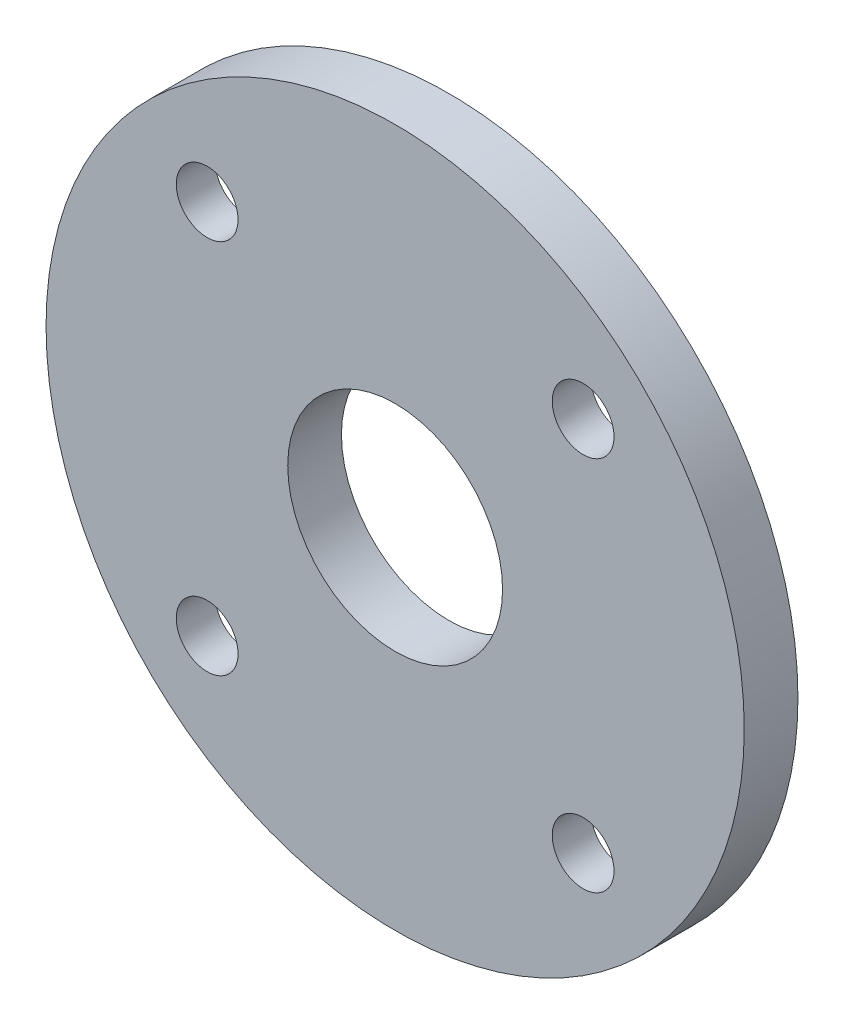
SolidWorks part; units mm, degrees
ref_plane "Front Plane" through (0, 0, 0) normal (0, 0, 1) x (1, 0, 0)
ref_plane "Top Plane" through (0, 0, 0) normal (0, 1, 0) x (1, 0, 0)
ref_plane "Right Plane" through (0, 0, 0) normal (1, 0, 0) x (0, 0, -1)
sketch "Cap_OD26_ID8_thickness2_profile" plane through (0, 0, 0) normal (0, 0, 1) x (1, 0, 0)
  circle A0 centre (0, 0) radius 13
  circle A1 centre (0, 0) radius 4
  dimension "D1" = 26
  dimension "D2" = 8
extrude "Cap_OD26_ID8_thickness2" add sketch "Cap_OD26_ID8_thickness2_profile" along normal blind 2
sketch "Four_M2_capture_holes_profile" plane through (0, 0, 0) normal (0, 0, 1) x (1, 0, 0)
  circle A0 centre (7, 7) radius 1.15
  circle A1 centre (-7, 7) radius 1.15
  circle A2 centre (-7, -7) radius 1.15
  circle A3 centre (7, -7) radius 1.15
  dimension "D1" = 2.3
  dimension "D2" = 2.3
  dimension "D3" = 2.3
  dimension "D4" = 2.3
extrude "Four_M2_capture_holes" cut sketch "Four_M2_capture_holes_profile" along normal through all from offset 50
sketch "Low_profile_head_seats" plane through (0, 0, 0) normal (0, 0, 1) x (1, 0, 0)
  circle A0 centre (7, 7) radius 2.1
  circle A1 centre (-7, 7) radius 2.1
  circle A2 centre (-7, -7) radius 2.1
  circle A3 centre (7, -7) radius 2.1
  dimension "D1" = 4.2
  dimension "D2" = 4.2
  dimension "D3" = 4.2
  dimension "D4" = 4.2
extrude "Head_recess_depth0p55" cut sketch "Low_profile_head_seats" along normal blind 0.55
